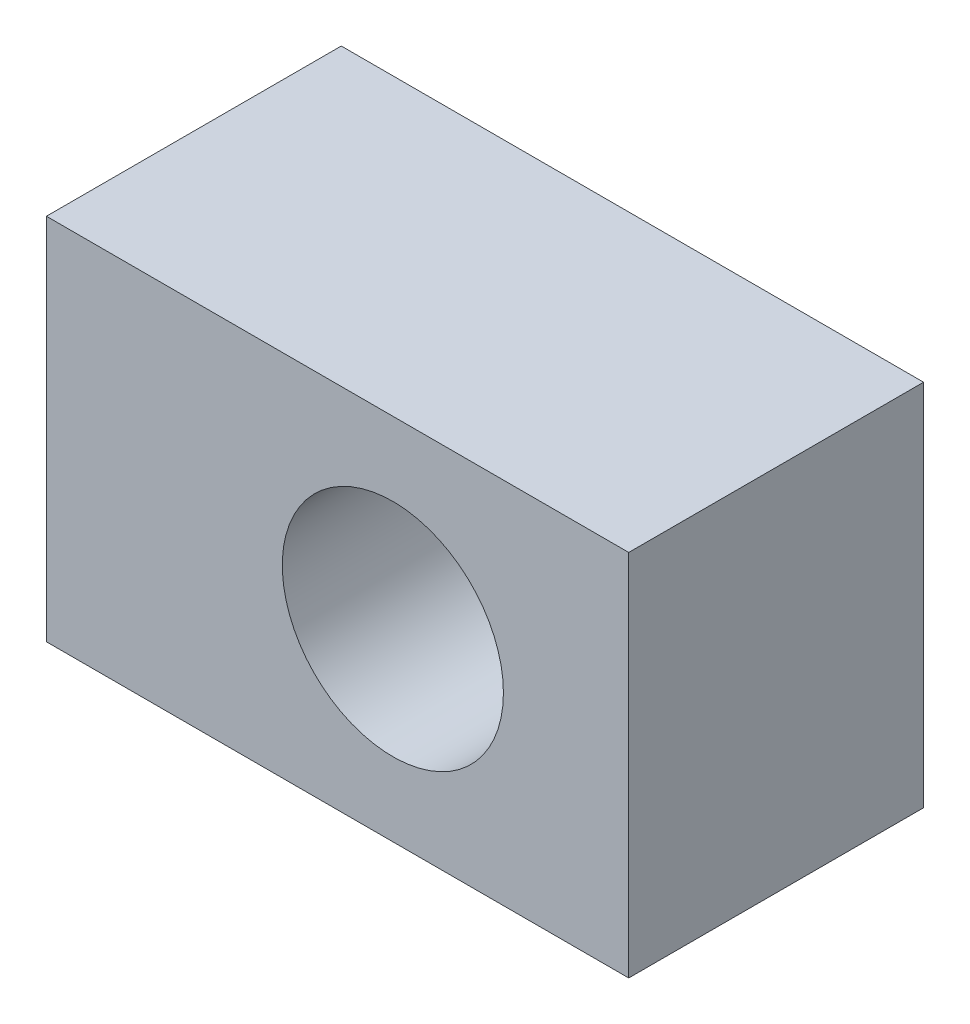
SolidWorks part; units mm, degrees
ref_plane "Front Plane" through (0, 0, 0) normal (0, 0, 1) x (1, 0, 0)
ref_plane "Top Plane" through (0, 0, 0) normal (0, 1, 0) x (1, 0, 0)
ref_plane "Right Plane" through (0, 0, 0) normal (1, 0, 0) x (0, 0, -1)
sketch "Sketch1" plane through (0, 0, 0) normal (0, 0, 1) x (1, 0, 0)
  line L1 (0, 0) -> (79, 0)
  line L2 (0, 0) -> (0, 50)
  line L3 (0, 50) -> (79, 50)
  line L4 (79, 0) -> (79, 50)
  circle A0 centre (47, 25) radius 15
  dimension "D3" = 30
  dimension "D4" = 47
  dimension "D1" = 79
  dimension "D2" = 50
  dimension "D5" = 25
extrude "Boss-Extrude1" add sketch "Sketch1" along normal blind 40
sketch "Sketch2" plane through (0, 0, 40) normal (0, 0, 1) x (1, 0, 0)
  line L0 (0, 50) -> (0, 0) construction
  line L1 (20, 26.5) -> (74, 26.5)
  line L2 (20, 26.5) -> (20, 0)
  line L3 (20, 0) -> (74, 0)
  line L4 (74, 26.5) -> (74, 0)
  dimension "D1" = 26.5
  dimension "D2" = 54
  dimension "D3" = 20
